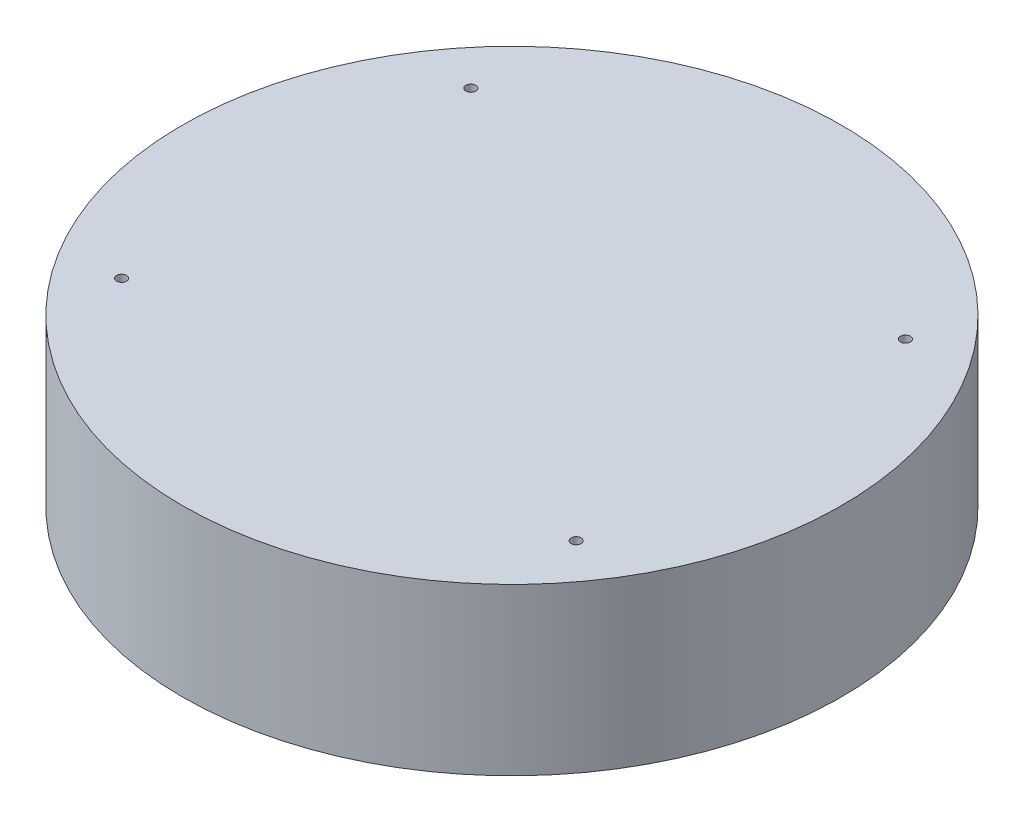
SolidWorks part; units mm, degrees
ref_plane "Front Plane" through (0, 0, 0) normal (0, 0, 1) x (1, 0, 0)
ref_plane "Top Plane" through (0, 0, 0) normal (0, 1, 0) x (1, 0, 0)
ref_plane "Right Plane" through (0, 0, 0) normal (1, 0, 0) x (0, 0, -1)
sketch "Sketch1" plane through (0, 0, 0) normal (0, 1, 0) x (1, 0, 0)
  circle A0 centre (0, 0) radius 164.95
  dimension "D1" = 329.9
extrude "Boss-Extrude1" add sketch "Sketch1" along normal blind 82.94
sketch "Sketch2" plane through (0, 82.94, 0) normal (0, 1, 0) x (1, 0, 0)
  line L0 (-108.75, 88.1671) -> (108.75, 88.1671) construction
  line L1 (-113.75, -81.6146) -> (113.75, -81.6146) construction
  line L2 (-140, 0) -> (140, 0) construction
  circle A0 centre (0, 0) radius 140
  circle A1 centre (-108.75, 88.1671) radius 2.5
  circle A2 centre (108.75, 88.1671) radius 2.5
  circle A3 centre (-113.75, -81.6146) radius 2.5
  circle A4 centre (113.75, -81.6146) radius 2.5
  dimension "D1" = 280
  dimension "D3" = 5
  dimension "D2" = 217.5
  dimension "D4" = 227.5
extrude "Cut-Extrude1" cut sketch "Sketch2" against normal blind 5 contours A1 | A2 | A4 | A3
